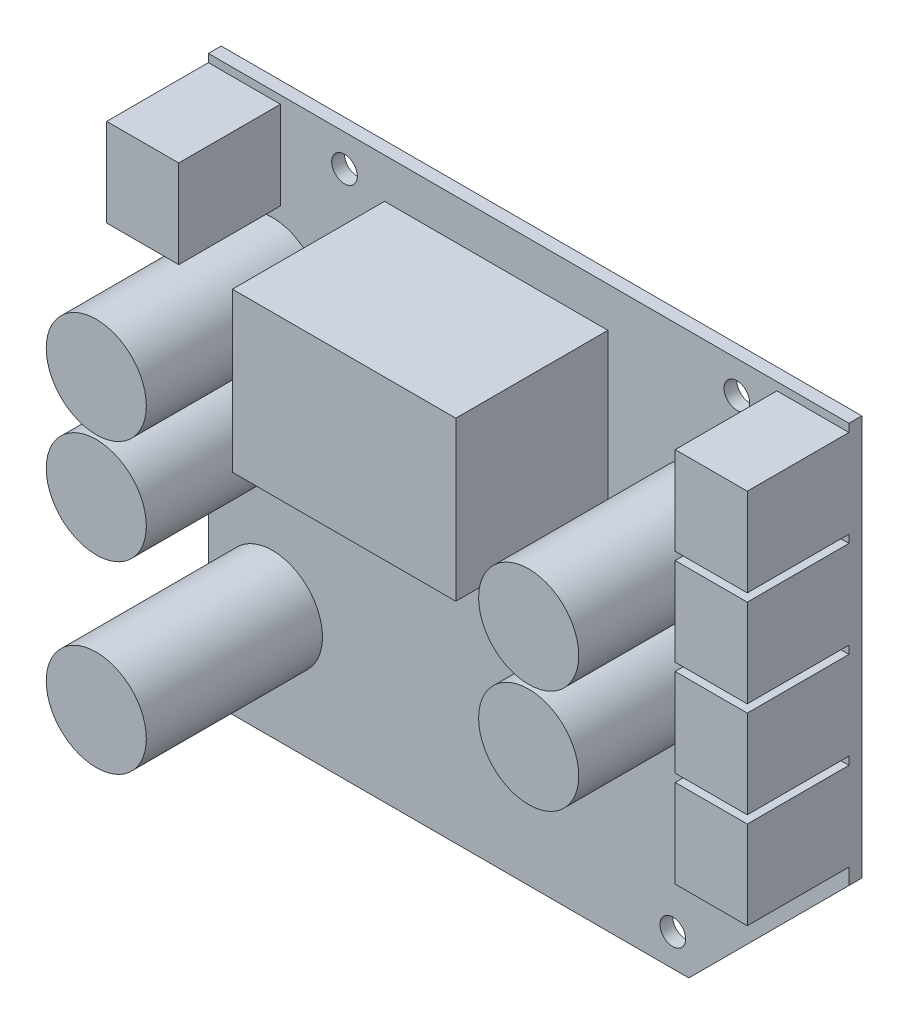
SolidWorks part; units mm, degrees
ref_plane "Plan de face" through (0, 0, 0) normal (0, 0, 1) x (1, 0, 0)
ref_plane "Plan de dessus" through (0, 0, 0) normal (0, 1, 0) x (1, 0, 0)
ref_plane "Plan de droite" through (0, 0, 0) normal (1, 0, 0) x (0, 0, -1)
sketch "Esquisse1" plane through (0, 0, 0) normal (0, 0, 1) x (1, 0, 0)
  line L0 (0, 0) -> (80, 0)
  line L1 (80, 0) -> (80, -50)
  line L2 (80, -50) -> (60, -70)
  line L3 (60, -70) -> (0, -70)
  line L4 (0, -70) -> (0, 0)
  circle A0 centre (17, -4) radius 1.6
  circle A1 centre (66, -4) radius 1.6
  circle A2 centre (58, -66) radius 1.6
  circle A3 centre (4, -66) radius 1.6
  point P14 (0, 0)
  point P15 (0, 0)
  point P16 (0, 0)
  dimension "D6" = 3.2
  dimension "D1" = 80
  dimension "D2" = 70
  dimension "D3" = 60
  dimension "D4" = 50
  dimension "D5" = 4
  dimension "D7" = 17
  dimension "D8" = 14
  dimension "D9" = 4
  dimension "D10" = 4
  dimension "D11" = 58
extrude "Boss.-Extru.1" add sketch "Esquisse1" along normal blind 1.6
sketch "Esquisse2" plane through (0, 0, 1.6) normal (0, 0, 1) x (1, 0, 0)
  line L0 (0, 0) -> (0, -70) construction
  line L1 (0, -1) -> (9, -1)
  line L2 (0, -1) -> (0, -12)
  line L3 (0, -12) -> (9, -12)
  line L4 (9, -1) -> (9, -12)
  line L5 (80, -50) -> (80, 0) construction
  line L6 (80, -1) -> (71, -1)
  line L7 (80, -1) -> (80, -12)
  line L8 (80, -12) -> (71, -12)
  line L9 (71, -1) -> (71, -12)
  line L10 (80, 0) -> (0, 0) construction
  line L11 (80, -13) -> (71, -13)
  line L12 (80, -13) -> (80, -24)
  line L13 (80, -24) -> (71, -24)
  line L14 (71, -13) -> (71, -24)
  line L15 (80, -25) -> (71, -25)
  line L16 (80, -25) -> (80, -36)
  line L17 (80, -36) -> (71, -36)
  line L18 (71, -25) -> (71, -36)
  line L19 (80, -37) -> (71, -37)
  line L20 (80, -37) -> (80, -48)
  line L21 (80, -48) -> (71, -48)
  line L22 (71, -37) -> (71, -48)
  point P24 (75.5, -37)
  point P25 (80, -18.5)
  dimension "D1" = 9
  dimension "D2" = 11
  dimension "D3" = 1
  dimension "D4" = 1
  dimension "D5" = 1
  dimension "D6" = 1
  dimension "D7" = 1
extrude "Boss.-Extru.2" add sketch "Esquisse2" along normal blind 12.7
sketch "Esquisse3" plane through (0, 0, 1.6) normal (0, 0, 1) x (1, 0, 0)
  line L0 (0, -12) -> (0, -70) construction
  line L1 (0, -12) -> (9, -12) construction
  line L2 (80, 0) -> (0, 0) construction
  line L3 (80, -1) -> (80, 0) construction
  circle A0 centre (8, -20) radius 6.25
  circle A1 centre (8, -33) radius 6.25
  circle A2 centre (8, -56) radius 6.25
  circle A3 centre (62, -20) radius 6.25
  circle A4 centre (62, -33) radius 6.25
  point P10 (0, 0)
  point P15 (0, 0)
  point P17 (8.9302, -38.5109)
  dimension "D1" = 12.5
  dimension "D2" = 8
  dimension "D3" = 8
  dimension "D4" = 13
  dimension "D5" = 23
  dimension "D6" = 20
  dimension "D7" = 13
  dimension "D8" = 18
extrude "Boss.-Extru.3" add sketch "Esquisse3" along normal blind 22
sketch "Esquisse4" plane through (0, 0, 1.6) normal (0, 0, 1) x (1, 0, 0)
  line L0 (80, 0) -> (0, 0) construction
  line L1 (22, -5) -> (49.9, -5)
  line L2 (22, -5) -> (22, -24.8)
  line L3 (22, -24.8) -> (49.9, -24.8)
  line L4 (49.9, -5) -> (49.9, -24.8)
  line L5 (0, -1) -> (0, -12) construction
  dimension "D1" = 27.9
  dimension "D2" = 19.8
  dimension "D3" = 5
  dimension "D4" = 22
extrude "Boss.-Extru.4" add sketch "Esquisse4" along normal blind 19
